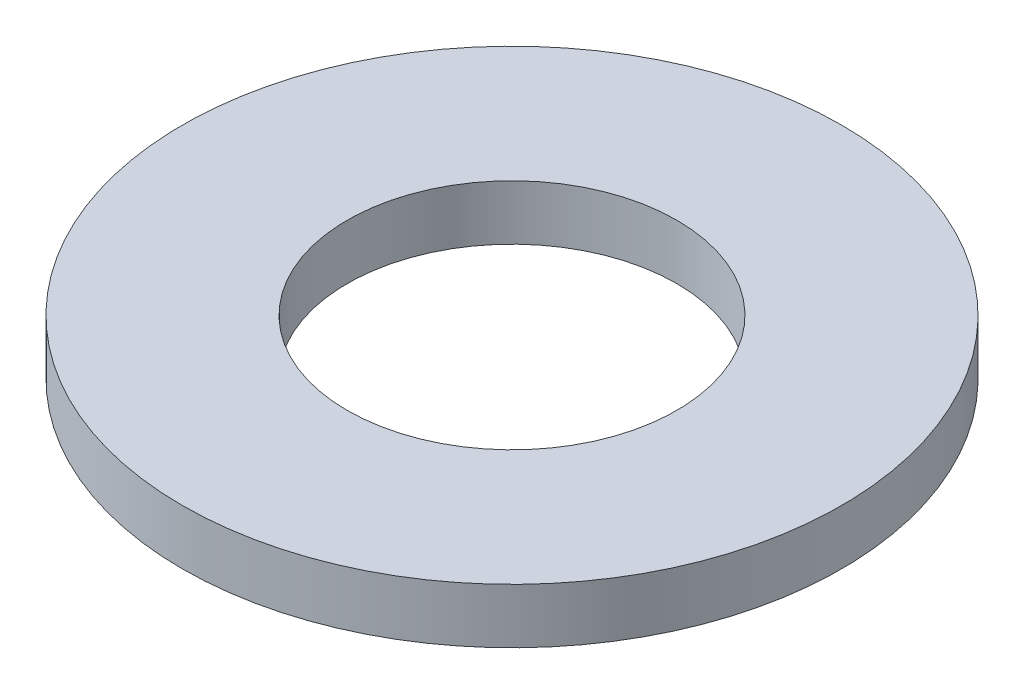
SolidWorks part; units mm, degrees
ref_plane "Front" through (0, 0, 0) normal (0, 0, 1) x (1, 0, 0)
ref_plane "Top" through (0, 0, 0) normal (0, 1, 0) x (1, 0, 0)
ref_plane "Right" through (0, 0, 0) normal (1, 0, 0) x (0, 0, -1)
sketch "Sketch1" plane through (0, 0, 0) normal (0, 1, 0) x (1, 0, 0)
  circle A0 centre (0, 0) radius 1.5
  circle A1 centre (0, 0) radius 3
extrude "Boss-Extrude1" add sketch "Sketch1" along normal blind 0.5
